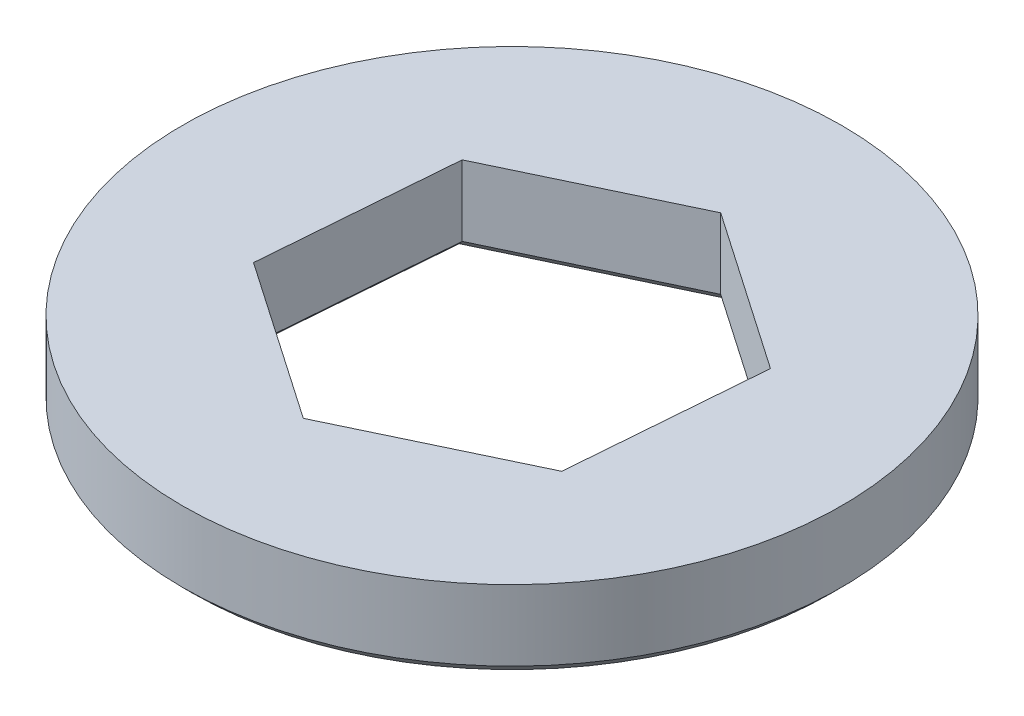
SolidWorks part; units mm, degrees
ref_plane "Front Plane" through (0, 0, 0) normal (0, 0, 1) x (1, 0, 0)
ref_plane "Top Plane" through (0, 0, 0) normal (0, 1, 0) x (1, 0, 0)
ref_plane "Right Plane" through (0, 0, 0) normal (1, 0, 0) x (0, 0, -1)
sketch "Sketch1" plane through (0, 0, 0) normal (0, 1, 0) x (1, 0, 0)
  line L1 (0.6037, 7.5971) -> (-6.2774, 4.3214)
  line L2 (-6.2774, 4.3214) -> (-6.8811, -3.2757)
  line L3 (-6.8811, -3.2757) -> (-0.6037, -7.5971)
  line L4 (-0.6037, -7.5971) -> (6.2774, -4.3214)
  line L5 (6.2774, -4.3214) -> (6.8811, 3.2757)
  line L6 (6.8811, 3.2757) -> (0.6037, 7.5971)
  circle A0 centre (0, 0) radius 6.6 construction
  circle A1 centre (0, 0) radius 12.95
  dimension "D1" = 13.2
  dimension "D2" = 6.35
extrude "Boss-Extrude1" add sketch "Sketch1" along normal blind 3.175
chamfer "Chamfer1" distance 0.4 angle 45 7 edges at (6.5793, 0, 0.5229) (2.8368, 0, 5.9592) (-3.7424, 0, 5.4364) (-6.5793, 0, -0.5229) (-2.8368, 0, -5.9592) (3.7424, 0, -5.4364) (0, 0, 12.95)
